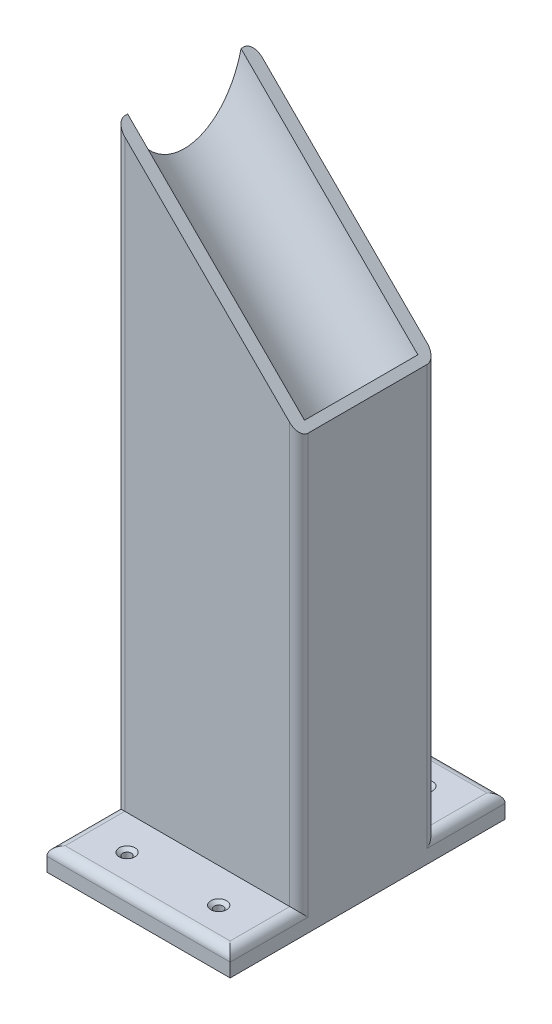
SolidWorks part; units mm, degrees
ref_plane "Front Plane" through (0, 0, 0) normal (0, 0, 1) x (1, 0, 0)
ref_plane "Top Plane" through (0, 0, 0) normal (0, 1, 0) x (1, 0, 0)
ref_plane "Right Plane" through (0, 0, 0) normal (1, 0, 0) x (0, 0, -1)
sketch "Sketch1" plane through (0, 0, 0) normal (0, 1, 0) x (1, 0, 0)
  line L1 (-106.7955, -38.1) -> (-157.5955, -38.1)
  line L2 (-106.7955, -38.1) -> (-106.7955, 38.1)
  line L3 (-106.7955, 38.1) -> (-157.5955, 38.1)
  line L4 (-157.5955, -38.1) -> (-157.5955, 38.1)
  line L5 (-106.7955, -38.1) -> (-157.5955, 38.1) construction
  line L6 (-106.7955, 38.1) -> (-157.5955, -38.1) construction
  point P0 (-132.1955, 0)
  dimension "D1" = 50.8
  dimension "D2" = 76.2
extrude "Boss-Extrude1" add sketch "Sketch1" along normal blind 6.35
sketch "Sketch2" plane through (0, 6.35, 0) normal (0, 1, 0) x (1, 0, 0)
  line L0 (-157.5955, 38.1) -> (-157.5955, -38.1) construction
  line L1 (-106.7955, -19.05) -> (-157.5955, -19.05)
  line L2 (-106.7955, -19.05) -> (-106.7955, 19.05)
  line L3 (-106.7955, 19.05) -> (-157.5955, 19.05)
  line L4 (-157.5955, -19.05) -> (-157.5955, 19.05)
  line L5 (-106.7955, -19.05) -> (-157.5955, 19.05) construction
  line L6 (-106.7955, 19.05) -> (-157.5955, -19.05) construction
  line L8 (-106.7955, -38.1) -> (-106.7955, 38.1) construction
  point P0 (-132.1955, 0)
  dimension "D1" = 38.1
extrude "Boss-Extrude2" add sketch "Sketch2" along normal blind 171.6066
sketch "Sketch5" plane through (0, 0, 19.05) normal (0, 0, 1) x (1, 0, 0)
  line L0 (-144.8955, 157.8906) -> (-118.328, 131.3231)
  line L1 (-144.8955, 157.8906) -> (-144.8955, 108.1657) construction
  line L2 (-157.5955, 177.9566) -> (-106.7955, 177.9566) construction
  dimension "D1" = 45
  dimension "D2" = 20.066
sketch "Sketch18" plane through (0, 0, -19.05) normal (0, 0, -1) x (-1, 0, 0)
  line L0 (157.5955, 177.9566) -> (157.5955, 155.4814) construction
  line L1 (157.5955, 177.9566) -> (157.5955, 6.35) construction
  line L2 (157.5955, 177.9566) -> (184.1058, 151.4463) construction
  dimension "D1" = 45
ref_plane "Plane1" through (-167.776, 167.776, 0) normal (0.7071, -0.7071, 0) x (-0.7071, -0.7071, 0)
sketch "Sketch19" plane through (-167.776, 167.776, 0) normal (0.7071, -0.7071, 0) x (-0.7071, -0.7071, 0)
  line L0 (16.3468, 0) -> (-14.3975, 0) construction
  line L1 (-14.3975, 16.51) -> (-14.3975, -16.51)
  line L2 (-14.3975, 19.05) -> (-14.3975, -49.2738) construction
  arc A0 (-14.3975, -16.51) -> (-14.3975, 16.51) centre (-14.3975, 0) ccw
  dimension "D1" = 33.02
extrude "Cut-Extrude1" cut sketch "Sketch19" against normal through all and the other way through all
ref_plane "Plane2" through (6.5885, 6.5885, 0) normal (-0.7071, -0.7071, 0) x (0, 0, 1)
other "SurfaceCut1"
sketch "Sketch20" plane through (6.5885, 6.5885, 0) normal (0.7071, 0.7071, 0) x (0, 0, -1)
  line L0 (19.05, 232.1911) -> (19.05, 160.3491) construction
  line L1 (-19.05, 160.3491) -> (19.05, 160.3491)
  line L2 (-19.05, 160.3491) -> (-19.05, 162.8891)
  line L3 (-19.05, 162.8891) -> (19.05, 162.8891)
  line L4 (19.05, 160.3491) -> (19.05, 162.8891)
  dimension "D1" = 2.54
extrude "Boss-Extrude3" add sketch "Sketch20" against normal up to surface up to face at (-132.1955, 141.3313, 3.9273)
sketch "Sketch22" plane through (-113.3839, 113.3839, 0) normal (0.7071, -0.7071, 0) x (0, 0, -1)
  line L0 (-15.709, 9.3175) -> (15.709, 9.3175)
  line L1 (-18.1618, 9.3175) -> (18.1618, 9.3175) construction
  arc A0 (-15.709, 9.3175) -> (15.709, 9.3175) centre (0, 14.3975) ccw construction
  arc A1 (-15.709, 9.3175) -> (15.709, 9.3175) centre (0, 14.3975) ccw construction
  arc A2 (15.709, 9.3175) -> (-15.709, 9.3175) centre (0, 9.3175) cw
extrude "Boss-Extrude4" add sketch "Sketch22" along normal up to surface up to face at (-106.7955, 60.2748, 1.905)
sketch "Sketch23" plane through (0, 6.35, 0) normal (0, 1, 0) x (1, 0, 0)
  line L0 (-106.7955, 28.575) -> (-157.5955, 28.575) construction
  line L1 (-106.7955, 19.05) -> (-106.7955, 38.1) construction
  line L2 (-157.5955, 38.1) -> (-157.5955, 19.05) construction
  line L3 (-132.1955, 38.1) -> (-132.1955, -38.1) construction
  line L4 (-106.7955, 38.1) -> (-157.5955, 38.1) construction
  line L5 (-157.5955, -38.1) -> (-106.7955, -38.1) construction
  line L6 (-106.7955, -28.575) -> (-157.5955, -28.575) construction
  line L7 (-106.7955, -38.1) -> (-106.7955, -19.05) construction
  line L8 (-157.5955, -19.05) -> (-157.5955, -38.1) construction
  line L9 (-144.8955, -19.05) -> (-144.8955, -38.1) construction
  line L10 (-157.5955, -19.05) -> (-106.7955, -19.05) construction
  line L11 (-119.4955, -19.05) -> (-119.4955, -38.1) construction
  line L12 (-157.5955, -38.1) -> (-144.8955, -38.1)
  dimension "D1" = 12.7
  dimension "D2" = 12.7
hole_wizard "CSK for #2 Flat Head Machine Screw (100)1" positions "Sketch26" profile "Sketch25" countersink size "#2" standard "ANSI Inch" end condition through all
sketch "Sketch26" plane through (0, 6.35, 0) normal (0, 1, 0) x (1, 0, 0)
  line L0 (-106.7955, -28.575) -> (-157.5955, -28.575) construction
  line L1 (-144.8955, -19.05) -> (-144.8955, -38.1) construction
  line L2 (-119.4955, -19.05) -> (-119.4955, -38.1) construction
  point P0 (-144.8955, -28.575)
  point P2 (-119.4955, -28.575)
sketch "Sketch25" plane through (-144.8955, 6.35, 28.575) normal (1, 0, 0) x (0, 0, 1)
  line L0 (0, 0) -> (0, 6.35)
  line L1 (0, 6.35) -> (1.2192, 6.35)
  line L2 (1.2192, 6.35) -> (1.2192, 0.8099)
  line L3 (1.2192, 0.8099) -> (2.1844, 0)
  line L5 (2.1844, 0) -> (0, 0)
  line L6 (-1.2192, 0.8099) -> (-2.1844, 0) construction
  line L11 (0, -6.35) -> (0, 107.95) construction
  dimension "Thru Hole Dia." = 2.4384
  dimension "Thru Hole Depth" = 6.35
  dimension "Near C'Sink Dia." = 4.3688
  dimension "Near C'Sink Angle" = 100
mirror "Mirror1" about plane through (0, 0, 0) normal (0, 0, 1) of "CSK for #2 Flat Head Machine Screw (100)1"
fillet "Fillet1" radius 2.54 4 edges
fillet "Fillet2" radius 2.54 6 edges at (-132.1955, 6.35, -38.1) (-132.1955, 6.35, 38.1)
sketch "Sketch27" plane through (-106.7955, 0, 0) normal (1, 0, 0) x (0, 0, -1)
  line L0 (-240.3842, 123.9915) -> (-35.0509, 123.9915) construction
